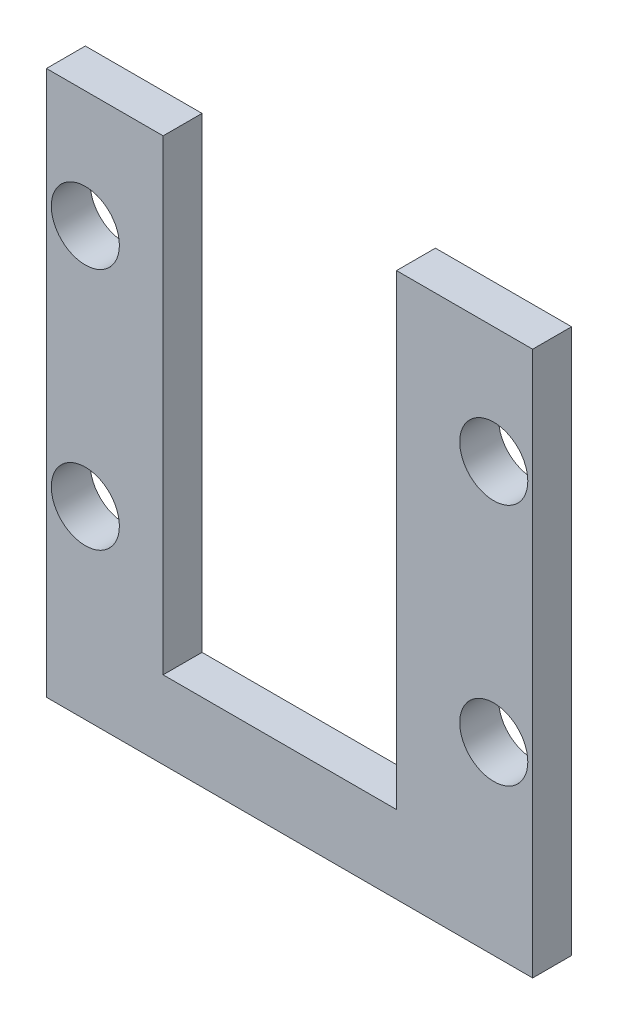
SolidWorks part; units mm, degrees
ref_plane "正面" through (0, 0, 0) normal (0, 0, 1) x (1, 0, 0)
ref_plane "平面" through (0, 0, 0) normal (0, 1, 0) x (1, 0, 0)
ref_plane "右側面" through (0, 0, 0) normal (1, 0, 0) x (0, 0, -1)
sketch "ｽｹｯﾁ1" plane through (0, 0, 0) normal (0, 0, 1) x (1, 0, 0)
  line L1 (0, 0) -> (25, 0)
  line L2 (0, 0) -> (0, 24)
  line L4 (25, 0) -> (25, 24)
  line L13 (6, 4) -> (18, 4)
  line L18 (6, 4) -> (6, 24)
  line L20 (18, 4) -> (18, 24)
  line L21 (0, 24) -> (6, 24)
  line L23 (0, 24) -> (0, 28)
  line L24 (0, 28) -> (6, 28)
  line L25 (6, 24) -> (6, 28)
  line L27 (18, 24) -> (18, 28)
  line L28 (18, 28) -> (25, 28)
  line L29 (25, 24) -> (25, 28)
  line L30 (18, 24) -> (25, 24)
  circle A0 centre (2, 22) radius 1.75
  circle A1 centre (23, 22) radius 1.75
  circle A2 centre (2, 9.5) radius 1.75
  circle A3 centre (23, 22) radius 1.75
  circle A6 centre (23, 9.5) radius 1.75
  dimension "D1" = 3.5
  dimension "D2" = 3.5
  dimension "D3" = 3.5
  dimension "D4" = 3.5
  dimension "D11" = 3.5
  dimension "D5" = 21
  dimension "D6" = 12.5
  dimension "D7" = 25
  dimension "D8" = 24
  dimension "D9" = 2
  dimension "D10" = 2
  dimension "D13" = 4
  dimension "D14" = 6
  dimension "D15" = 28
  dimension "D16" = 7
  dimension "D17" = 28
  dimension "D18" = 6
extrude "ﾎﾞｽ - 押し出し6" add sketch "ｽｹｯﾁ1" along normal blind 2 contours L30 L20 L13 L18 L21 L2 L1 L4 A6 A2 A1 A0 | L21 L25 L24 L23 | L27 L30 L29 L28
